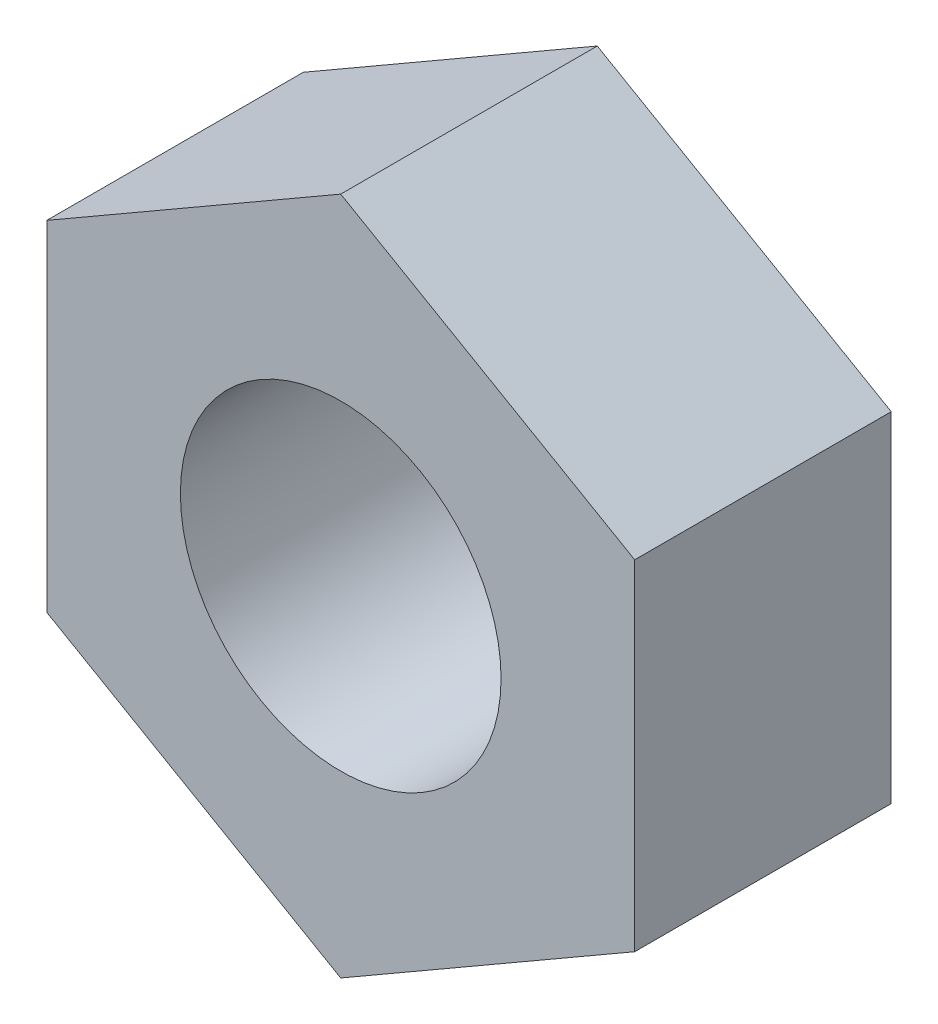
SolidWorks part; units mm, degrees
ref_plane "前视基准面" through (0, 0, 0) normal (0, 0, 1) x (1, 0, 0)
ref_plane "上视基准面" through (0, 0, 0) normal (0, 1, 0) x (1, 0, 0)
ref_plane "右视基准面" through (0, 0, 0) normal (1, 0, 0) x (0, 0, -1)
other "Configuration Table"
sketch "草图1" plane through (0, 0, 0) normal (0, 0, 1) x (1, 0, 0)
  line L0 (2.75, 1.5877) -> (0, 3.1754)
  line L1 (0, 3.1754) -> (-2.75, 1.5877)
  line L2 (-2.75, 1.5877) -> (-2.75, -1.5877)
  line L3 (-2.75, -1.5877) -> (0, -3.1754)
  line L4 (0, -3.1754) -> (2.75, -1.5877)
  line L5 (2.75, -1.5877) -> (2.75, 1.5877)
  circle A0 centre (0, 0) radius 1.5
extrude "Nut_simplified" add sketch "草图1" along normal blind 2.4
